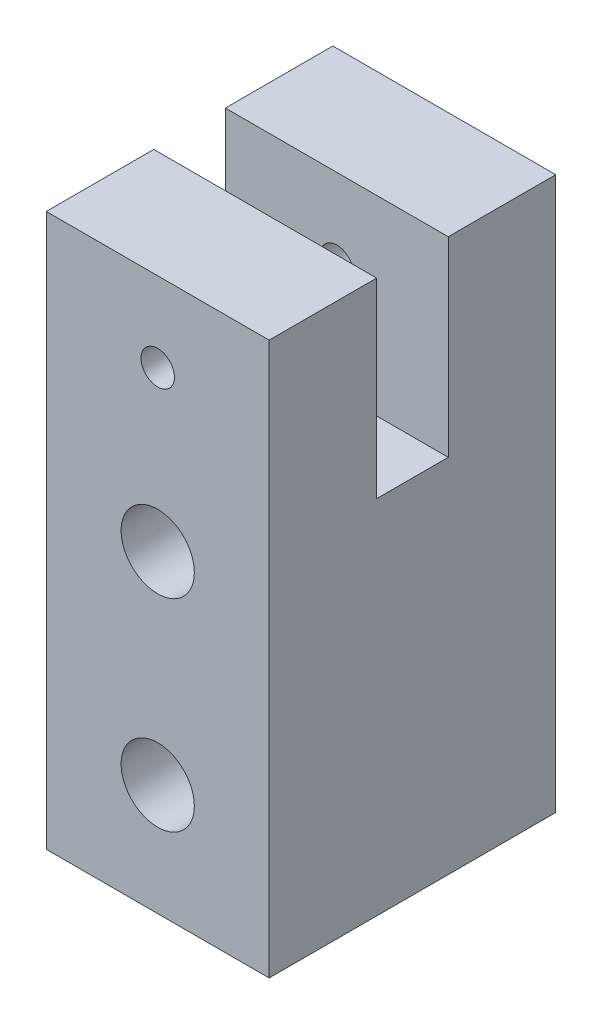
SolidWorks part; units mm, degrees
ref_plane "Front Plane" through (0, 0, 0) normal (0, 0, 1) x (1, 0, 0)
ref_plane "Top Plane" through (0, 0, 0) normal (0, 1, 0) x (1, 0, 0)
ref_plane "Right Plane" through (0, 0, 0) normal (1, 0, 0) x (0, 0, -1)
sketch "Sketch2" plane through (0, 0, 0) normal (0, 0, 1) x (1, 0, 0)
  line L1 (-7, -17.35) -> (7, -17.35)
  line L2 (-7, -17.35) -> (-7, 17.35)
  line L3 (-7, 17.35) -> (7, 17.35)
  line L4 (7, -17.35) -> (7, 17.35)
  line L5 (-7, -17.35) -> (7, 17.35) construction
  line L6 (-7, 17.35) -> (7, -17.35) construction
  point P0 (0, 0)
  dimension "D1" = 14
  dimension "D2" = 34.7
extrude "Boss-Extrude1" add sketch "Sketch2" along normal blind 18
sketch "Sketch3" plane through (0, 0, 18) normal (0, 0, 1) x (1, 0, 0)
  line L0 (-7, -17.35) -> (7, -17.35) construction
  circle A0 centre (0, -10.35) radius 2.3
  circle A1 centre (0, 2.35) radius 2.3
  dimension "D1" = 7
  dimension "D2" = 12.7
  dimension "D3" = 4.6
  dimension "D4" = 4.6
extrude "Cut-Extrude1" cut sketch "Sketch3" against normal through all
sketch "Sketch4" plane through (7, 0, 0) normal (1, 0, 0) x (0, 0, -1)
  line L0 (-18, 17.35) -> (0, 17.35) construction
  line L1 (-11.25, 5.35) -> (-6.75, 5.35)
  line L2 (-11.25, 5.35) -> (-11.25, 17.35)
  line L3 (-11.25, 17.35) -> (-6.75, 17.35)
  line L4 (-6.75, 5.35) -> (-6.75, 17.35)
  line L5 (-11.25, 5.35) -> (-6.75, 17.35) construction
  line L6 (-11.25, 17.35) -> (-6.75, 5.35) construction
  line L7 (0, -17.35) -> (0, 17.35) construction
  point P0 (-9, 11.35)
  dimension "D1" = 4.5
  dimension "D2" = 6.75
  dimension "D3" = 12
extrude "Cut-Extrude2" cut sketch "Sketch4" against normal blind 8
sketch "Sketch5" plane through (0, 0, 18) normal (0, 0, 1) x (1, 0, 0)
  line L0 (7, 17.35) -> (-7, 17.35) construction
  circle A0 centre (0, 12.35) radius 1.05
  dimension "D1" = 5
extrude "Cut-Extrude3" cut sketch "Sketch5" against normal through all
sketch "Sketch8" plane through (7, 0, 0) normal (1, 0, 0) x (0, 0, -1)
  line L0 (-11.25, 17.35) -> (-11.25, 5.35) construction
  line L1 (-6.75, 17.35) -> (-11.25, 17.35)
  line L2 (-6.75, 17.35) -> (-6.75, 10.35)
  line L3 (-6.75, 10.35) -> (-11.25, 10.35)
  line L4 (-11.25, 17.35) -> (-11.25, 10.35)
  dimension "D1" = 7
extrude "Cut-Extrude6" cut sketch "Sketch8" against normal through all
